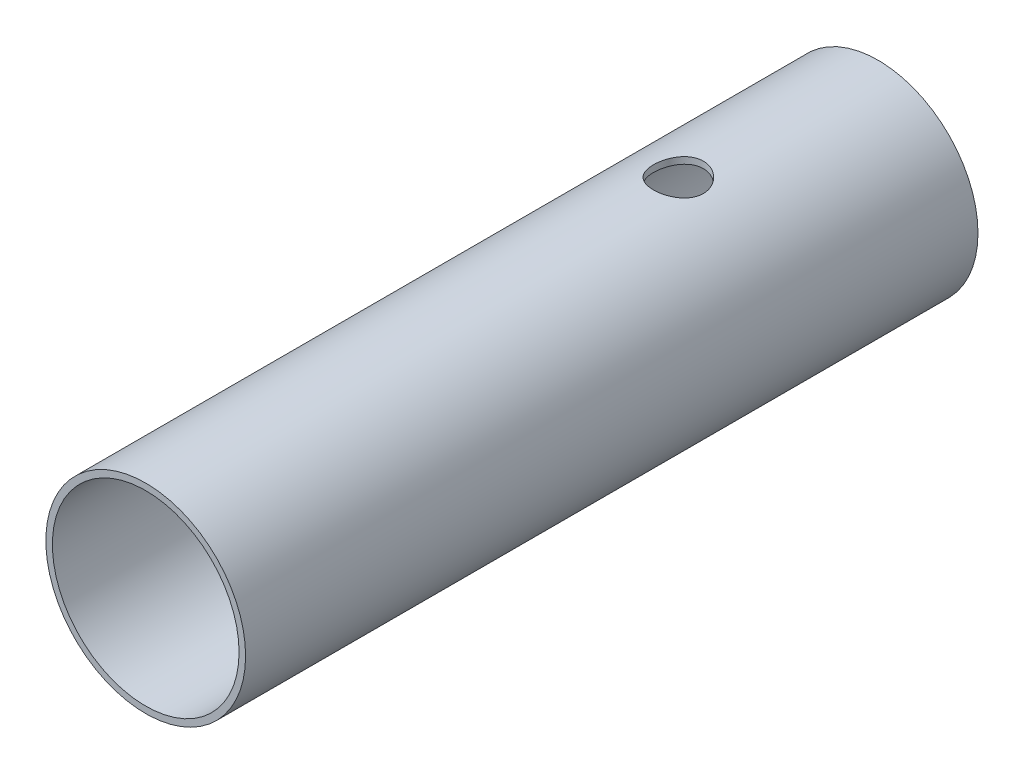
SolidWorks part; units mm, degrees
ref_plane "Front Plane" through (0, 0, 0) normal (0, 0, 1) x (1, 0, 0)
ref_plane "Top Plane" through (0, 0, 0) normal (0, 1, 0) x (1, 0, 0)
ref_plane "Right Plane" through (0, 0, 0) normal (1, 0, 0) x (0, 0, -1)
sketch "Sketch1" plane through (0, 0, 0) normal (0, 0, 1) x (1, 0, 0)
  circle A0 centre (0, 0) radius 19.05 construction
  circle A1 centre (0, 0) radius 17.8054 construction
  point P3 (-19.05, 0)
  point P4 (19.05, 0)
  point P6 (-17.8054, 0)
  point P7 (17.8054, 0)
  dimension "OD" = 38.1
  dimension "Wall" = 1.2446
  dimension "ID" = 35.6108
sketch "Sketch2" plane through (0, 0, 0) normal (1, 0, 0) x (0, 0, -1)
  line L0 (69.85, 0) -> (-69.85, 0) construction
  line L2 (0, 19.05) -> (0, -19.05) construction
  line L3 (0, 19.05) -> (0, -19.05) construction
  line L4 (69.85, 19.05) -> (-69.85, 19.05) construction
  line L5 (69.85, -19.05) -> (-69.85, -19.05) construction
  line L6 (-69.85, -19.05) -> (-69.85, 19.05) construction
  line L7 (69.85, -19.05) -> (69.85, 19.05) construction
  line L8 (-31.75, -19.05) -> (-31.75, 19.05) construction
  line L9 (31.75, -19.05) -> (31.75, 19.05) construction
  point P3 (0, 0)
  point P9 (0, 19.05)
  point P11 (0, -19.05)
  point P13 (-69.85, 0)
  point P14 (69.85, 19.05)
  point P15 (-69.85, -19.05)
  point P16 (-69.85, 19.05)
  point P17 (-69.85, 0)
  point P18 (69.85, -19.05)
  point P19 (69.85, 0)
  point P22 (-31.75, 0)
  point P25 (31.75, 0)
  point P26 (-31.75, -19.05)
  point P27 (-31.75, 19.05)
  point P28 (31.75, 19.05)
  point P29 (31.75, -19.05)
  dimension "Length" = 139.7
  dimension "D1" = 38.1
sketch "Sketch3" plane through (0, 0, 0) normal (0, 0, 1) x (1, 0, 0)
  circle A0 centre (0, 0) radius 19.05 construction
  circle A1 centre (0, 0) radius 17.8054 construction
  circle A2 centre (0, 0) radius 19.05
  circle A3 centre (0, 0) radius 17.8054
extrude "Boss-Extrude1" add sketch "Sketch3" along normal mid plane 139.7
ref_plane "Plane1" through (0, 25.4, 0) normal (0, 1, 0) x (1, 0, 0)
sketch "Sketch4" plane through (0, 25.4, 0) normal (0, 1, 0) x (1, 0, 0)
  line L0 (17.8054, 69.85) -> (-17.8054, 69.85) construction
  circle A0 centre (0, 31.75) radius 4.7625
  dimension "D1" = 9.525
  dimension "D2" = 38.1
extrude "Cut-Extrude1" cut sketch "Sketch4" against normal through all
equation "\"D1@Sketch2\"=\"OD@Sketch1\""
equation "\"D1@Boss-Extrude1\"=\"Length@Sketch2\""
